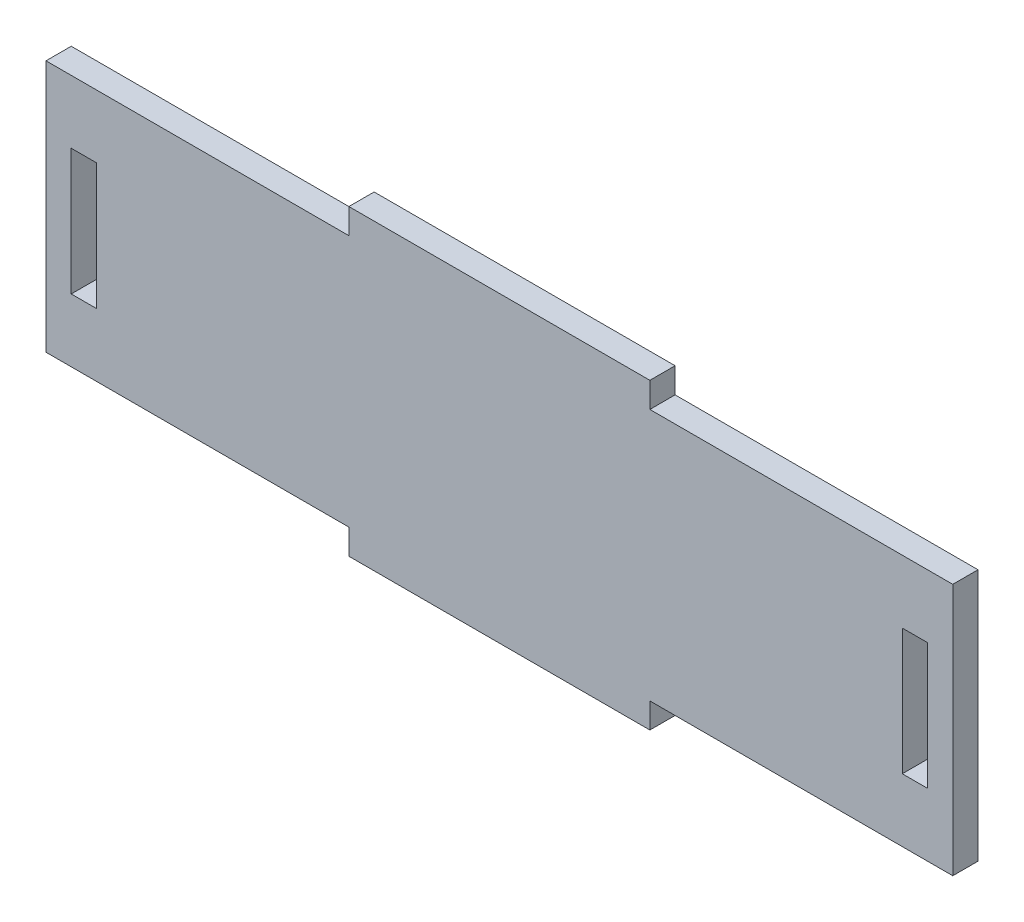
SolidWorks part; units mm, degrees
ref_plane "Front Plane" through (0, 0, 0) normal (0, 0, 1) x (1, 0, 0)
ref_plane "Top Plane" through (0, 0, 0) normal (0, 1, 0) x (1, 0, 0)
ref_plane "Right Plane" through (0, 0, 0) normal (1, 0, 0) x (0, 0, -1)
sketch "Sketch1" plane through (0, 0, 0) normal (0, 0, 1) x (1, 0, 0)
  line L0 (0, 0) -> (24, 0)
  line L2 (0, 0) -> (0, 20)
  line L4 (71.848, 0) -> (71.848, 20)
  line L5 (24, 0) -> (24, -2)
  line L6 (24, -2) -> (47.848, -2)
  line L7 (47.848, -2) -> (47.848, 0)
  line L8 (47.848, 0) -> (71.848, 0)
  line L9 (0, 20) -> (24, 20)
  line L10 (24, 20) -> (24, 22)
  line L11 (24, 22) -> (47.848, 22)
  line L12 (47.848, 22) -> (47.848, 20)
  line L13 (47.848, 20) -> (71.848, 20)
  line L19 (2, 15) -> (4, 15)
  line L20 (2, 15) -> (2, 5)
  line L21 (2, 5) -> (4, 5)
  line L22 (4, 15) -> (4, 5)
  line L23 (67.848, 15) -> (69.848, 15)
  line L24 (67.848, 15) -> (67.848, 5)
  line L25 (67.848, 5) -> (69.848, 5)
  line L26 (69.848, 15) -> (69.848, 5)
  dimension "D1" = 20
  dimension "D2" = 5
  dimension "D3" = 5
  dimension "D6" = 2
  dimension "D7" = 5
  dimension "D8" = 5
  dimension "D9" = 2
extrude "Boss-Extrude1" add sketch "Sketch1" along normal blind 2
